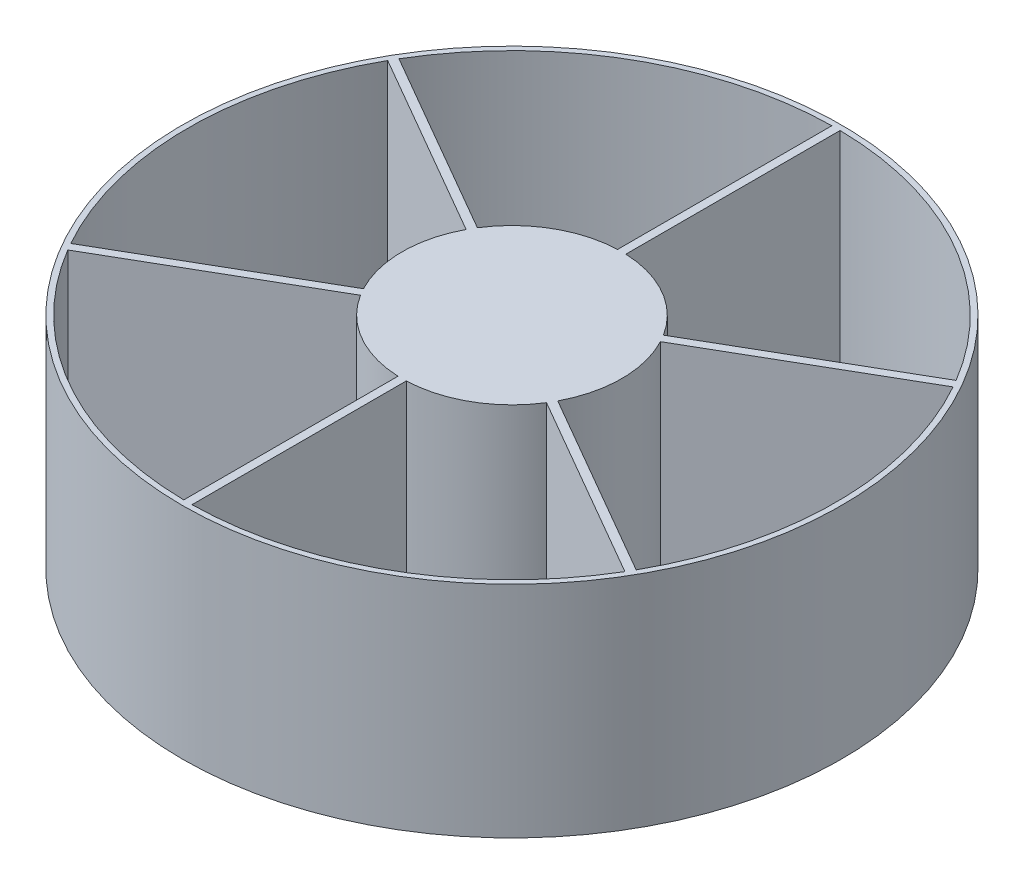
SolidWorks part; units mm, degrees
ref_plane "前视基准面" through (0, 0, 0) normal (0, 0, 1) x (1, 0, 0)
ref_plane "上视基准面" through (0, 0, 0) normal (0, 1, 0) x (1, 0, 0)
ref_plane "右视基准面" through (0, 0, 0) normal (1, 0, 0) x (0, 0, -1)
other "Configuration Table"
sketch "草图1" plane through (0, 0, 0) normal (0, 1, 0) x (1, 0, 0)
  circle A0 centre (0, 0) radius 120
  circle A1 centre (0, 0) radius 38
  dimension "D1" = 240
  dimension "D2" = 76
extrude "凸台-拉伸1" add sketch "草图1" along normal blind 80
shell "抽壳1" thickness 2
sketch "草图2" plane through (0, 80, 0) normal (0, 1, 0) x (1, 0, 0)
  line L0 (-1.5, 117.9905) -> (-1.5, 39.9719)
  line L1 (1.5, 117.9905) -> (1.5, 39.9719)
  circle A0 centre (0, 0) radius 118 construction
  circle A1 centre (0, 0) radius 40 construction
  circle A2 centre (0, 0) radius 118 construction
  circle A3 centre (0, 0) radius 40 construction
  arc A4 (-1.5, 117.9905) -> (1.5, 117.9905) centre (0, 0) cw
  arc A5 (-1.5, 39.9719) -> (1.5, 39.9719) centre (0, 0) cw
  dimension "3" = 3
extrude "凸台-拉伸2" add sketch "草图2" against normal up to surface (78 mm away) up to face at (0, 2, 118)
pattern_circular "阵列(圆周)1" count 6 over 360 about axis through (0, 0, 0) along (0, 1, 0) of "凸台-拉伸2"
sketch "草图3" plane through (0, 80, 0) normal (0, 1, 0) x (1, 0, 0)
  circle A0 centre (0, 0) radius 38 construction
  circle A1 centre (0, 0) radius 38
extrude "凸台-拉伸3" add sketch "草图3" against normal blind 8
sketch "草图4" plane through (0, 72, 0) normal (0, -1, 0) x (1, 0, 0)
  circle A0 centre (0, 0) radius 5
  dimension "D1" = 10
extrude "凸台-拉伸4" add sketch "草图4" along normal blind 24
sketch "草图5" plane through (0, 48, 0) normal (0, -1, 0) x (1, 0, 0)
  line L0 (-2.0494, 1.6) -> (-2.0494, -1.6)
  arc A0 (-2.0494, -1.6) -> (-2.0494, 1.6) centre (0, 0) ccw
  dimension "D1" = 3.2
  dimension "D2" = 5.2
extrude "切除-拉伸1" cut sketch "草图5" against normal offset from surface (19 mm away) 19 up to face at (0, 48, -5)
sketch "草图6" plane through (0, 72, 0) normal (0, -1, 0) x (1, 0, 0)
  circle A0 centre (0, 0) radius 5 construction
  circle A1 centre (0, 0) radius 38
  circle A2 centre (0, 0) radius 38
  circle A3 centre (0, 0) radius 5
  dimension "D1" = 0
extrude "切除-拉伸2" cut sketch "草图6" against normal blind 3
